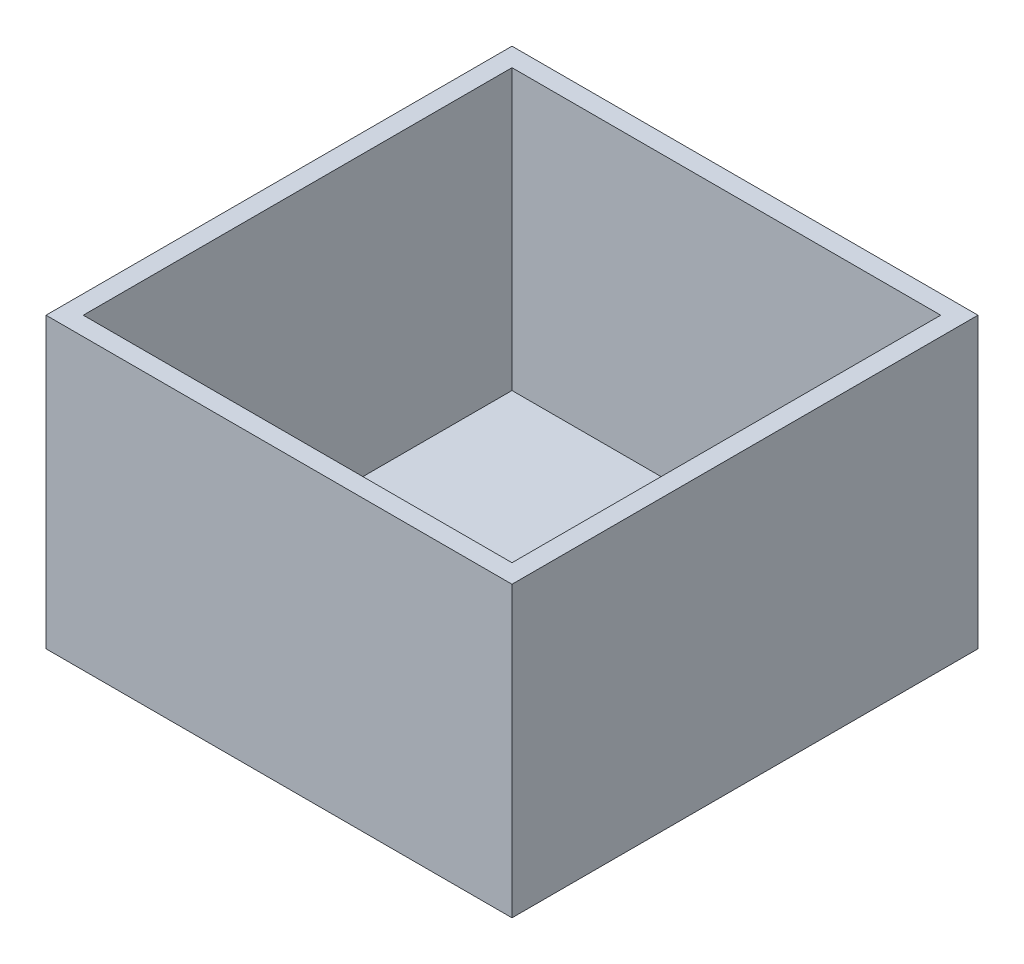
SolidWorks part; units mm, degrees
ref_plane "Ön Düzlem" through (0, 0, 0) normal (0, 0, 1) x (1, 0, 0)
ref_plane "Üst Düzlem" through (0, 0, 0) normal (0, 1, 0) x (1, 0, 0)
ref_plane "Sağ Düzlem" through (0, 0, 0) normal (1, 0, 0) x (0, 0, -1)
sketch "Çizim1" plane through (0, 0, 0) normal (0, 1, 0) x (1, 0, 0)
  line L0 (-23, 23) -> (23, 23)
  line L1 (-25, -25) -> (25, -25)
  line L2 (-25, -25) -> (-25, 25)
  line L3 (-25, 25) -> (25, 25)
  line L4 (25, -25) -> (25, 25)
  line L5 (-25, -25) -> (25, 25) construction
  line L6 (-25, 25) -> (25, -25) construction
  line L7 (23, -23) -> (23, 23)
  line L8 (-23, -23) -> (23, -23)
  line L9 (-23, -23) -> (-23, 23)
  point P0 (0, 0)
  dimension "D2" = 50
  dimension "D3" = 50
  dimension "D1" = 2
extrude "Yükseklik-Ekstrüzyon1" add sketch "Çizim1" along normal blind 30
sketch "Çizim2" plane through (0, 0, 0) normal (0, -1, 0) x (1, 0, 0)
  line L1 (-25, -25) -> (25, -25)
  line L2 (-25, -25) -> (-25, 25)
  line L3 (-25, 25) -> (25, 25)
  line L4 (25, -25) -> (25, 25)
  line L5 (-25, -25) -> (25, 25) construction
  line L6 (-25, 25) -> (25, -25) construction
  point P0 (0, 0)
extrude "Yükseklik-Ekstrüzyon2" add sketch "Çizim2" along normal blind 1
